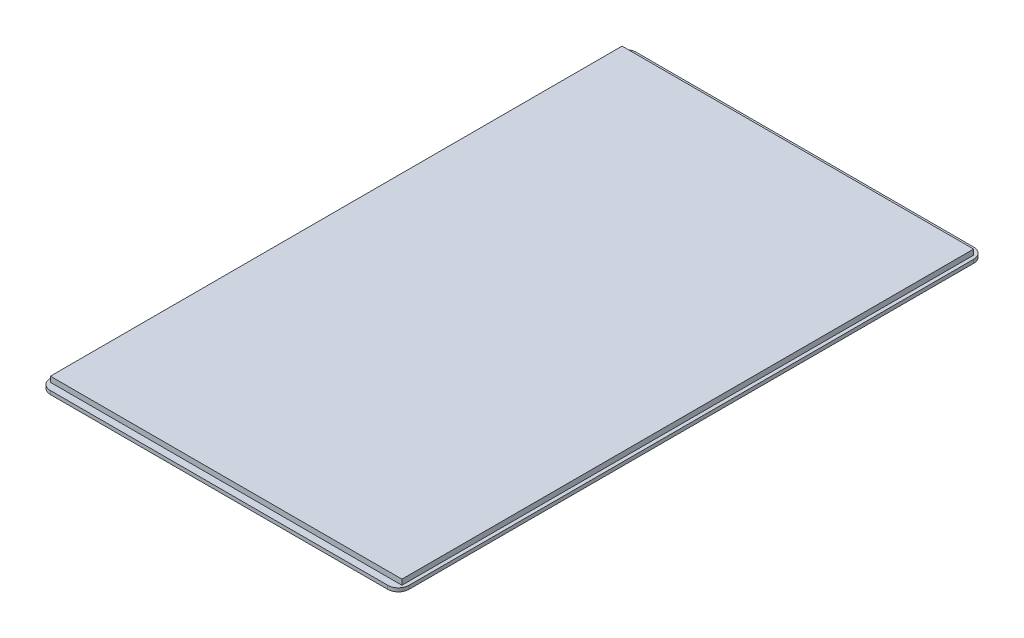
SolidWorks part; units mm, degrees
ref_plane "Front Plane" through (0, 0, 0) normal (0, 0, 1) x (1, 0, 0)
ref_plane "Top Plane" through (0, 0, 0) normal (0, 1, 0) x (1, 0, 0)
ref_plane "Right Plane" through (0, 0, 0) normal (1, 0, 0) x (0, 0, -1)
sketch "Sketch1" plane through (0, 0, 0) normal (0, 1, 0) x (1, 0, 0)
  line L1 (-50.5, 82.5) -> (50.5, 82.5)
  line L2 (-50.5, 82.5) -> (-50.5, -82.5)
  line L3 (-50.5, -82.5) -> (50.5, -82.5)
  line L4 (50.5, 82.5) -> (50.5, -82.5)
  line L5 (-50.5, 82.5) -> (50.5, -82.5) construction
  line L6 (-50.5, -82.5) -> (50.5, 82.5) construction
  point P0 (0, 0)
  dimension "D1" = 101
  dimension "D2" = 165
extrude "Boss-Extrude1" add sketch "Sketch1" along normal blind 1
sketch "Sketch2" plane through (0, 1, 0) normal (0, 1, 0) x (1, 0, 0)
  line L1 (-49.5, 80.5) -> (49.5, 80.5)
  line L2 (-49.5, 80.5) -> (-49.5, -80.5)
  line L3 (-49.5, -80.5) -> (49.5, -80.5)
  line L4 (49.5, 80.5) -> (49.5, -80.5)
  line L5 (-49.5, 80.5) -> (49.5, -80.5) construction
  line L6 (-49.5, -80.5) -> (49.5, 80.5) construction
  point P0 (0, 0)
  point P5 (0, 0)
  point P6 (0, 0)
  dimension "D1" = 99
  dimension "D2" = 161
extrude "Boss-Extrude2" add sketch "Sketch2" along normal blind 1.5
fillet "Fillet1" radius 3 4 edges at (-50.5, 0.5, 82.5) (50.5, 0.5, 82.5) (50.5, 0.5, -82.5) (-50.5, 0.5, -82.5)
